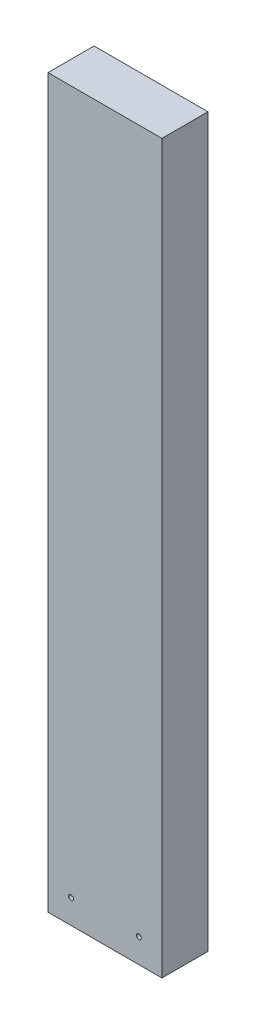
SolidWorks part; units mm, degrees
ref_plane "Front Plane" through (0, 0, 0) normal (0, 0, 1) x (1, 0, 0)
ref_plane "Top Plane" through (0, 0, 0) normal (0, 1, 0) x (1, 0, 0)
ref_plane "Right Plane" through (0, 0, 0) normal (1, 0, 0) x (0, 0, -1)
sketch "Sketch1" plane through (0, 0, 0) normal (0, 0, 1) x (1, 0, 0)
  line L0 (0, 199.5602) -> (0, -264.2102) construction
  line L1 (-23.5, 150) -> (23.5, 150)
  line L2 (-23.5, 150) -> (-23.5, -150)
  line L3 (-23.5, -150) -> (23.5, -150)
  line L4 (23.5, 150) -> (23.5, -150)
  line L5 (-45.1983, 0) -> (43.1762, 0) construction
  line L6 (-38.2115, -140) -> (39.2079, -140) construction
  line L7 (-14, -133.9217) -> (-14, -148.8474) construction
  line L8 (14, -133.9217) -> (14, -148.8474) construction
  circle A0 centre (-14, -140) radius 1
  circle A2 centre (14, -140) radius 1
  dimension "D6" = 2
  dimension "D8" = 2
  dimension "D1" = 300
  dimension "D2" = 47
  dimension "D3" = 10
  dimension "D4" = 14
  dimension "D5" = 14
extrude "Boss-Extrude1" add sketch "Sketch1" along normal blind 19
